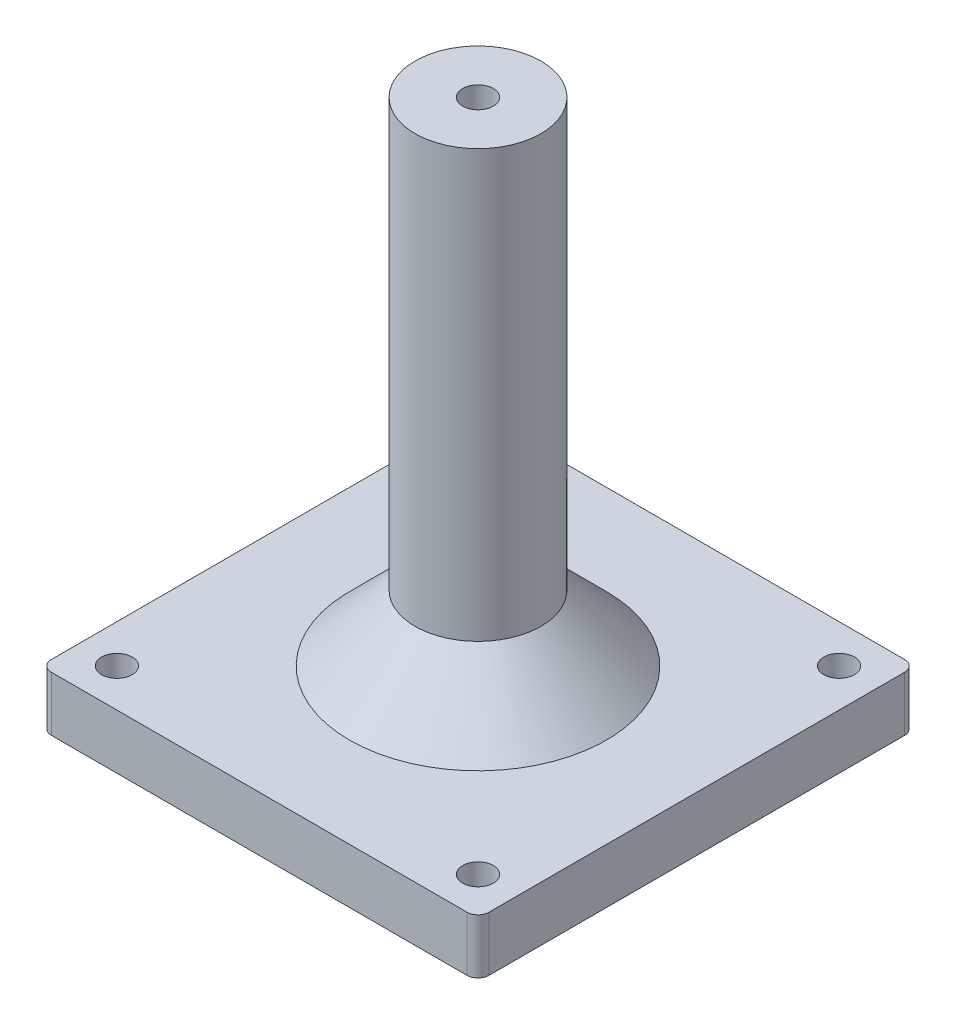
SolidWorks part; units mm, degrees
ref_plane "Front Plane" through (0, 0, 0) normal (0, 0, 1) x (1, 0, 0)
ref_plane "Top Plane" through (0, 0, 0) normal (0, 1, 0) x (1, 0, 0)
ref_plane "Right Plane" through (0, 0, 0) normal (1, 0, 0) x (0, 0, -1)
sketch "Sketch1" plane through (0, 0, 0) normal (0, 1, 0) x (1, 0, 0)
  line L1 (-20, 20) -> (20, 20)
  line L2 (-20, 20) -> (-20, -20)
  line L3 (-20, -20) -> (20, -20)
  line L4 (20, 20) -> (20, -20)
  line L5 (-20, 20) -> (20, -20) construction
  line L6 (-20, -20) -> (20, 20) construction
  circle A0 centre (0, 0) radius 6 construction
  circle A1 centre (0, 0) radius 10 construction
  point P0 (0, 0)
  dimension "D3" = 12
  dimension "D4" = 4
  dimension "D1" = 40
  dimension "D2" = 40
extrude "Boss-Extrude1" add sketch "Sketch1" along normal blind 5
sketch "Sketch3" plane through (0, 0, 0) normal (0, -1, 0) x (1, 0, 0)
  line L0 (-16.5, 16.5) -> (-16.5, -16.5) construction
  line L1 (-16.5, -16.5) -> (16.5, -16.5) construction
  line L2 (16.5, -16.5) -> (16.5, 16.5) construction
  line L3 (16.5, 16.5) -> (-16.5, 16.5) construction
  line L4 (20, -20) -> (20, 20)
  line L5 (20, 20) -> (-20, 20)
  line L6 (-20, 20) -> (-20, -20)
  line L7 (-20, -20) -> (20, -20)
  line L8 (20, -20) -> (20, 20) construction
  line L9 (20, 20) -> (-20, 20) construction
  line L10 (-20, 20) -> (-20, -20) construction
  line L11 (-20, -20) -> (20, -20) construction
  circle A0 centre (-16.5, -16.5) radius 1.4
  circle A1 centre (-16.5, 16.5) radius 1.4
  circle A2 centre (16.5, 16.5) radius 1.4
  circle A3 centre (16.5, -16.5) radius 1.4
  dimension "D3" = 2.8
  dimension "D1" = 0
  dimension "D2" = 3.5
extrude "Cut-Extrude1" cut sketch "Sketch3" against normal blind 10
sketch "Sketch4" plane through (0, 5, 0) normal (0, 1, 0) x (1, 0, 0)
  circle A0 centre (0, 0) radius 5.75
  dimension "D1" = 11.5
extrude "Boss-Extrude2" add sketch "Sketch4" along normal blind 45
sketch "Sketch5" plane through (0, 50, 0) normal (0, 1, 0) x (1, 0, 0)
  circle A0 centre (0, 0) radius 7.375
  dimension "D1" = 14.75
chamfer "Chamfer1" distance 6 angle 45 1 edges at (0, 5, 5.75)
sketch "Sketch6" plane through (0, 50, 0) normal (0, 1, 0) x (1, 0, 0)
  circle A0 centre (0, 0) radius 1.4
  dimension "D1" = 2.8
extrude "Cut-Extrude2" cut sketch "Sketch6" against normal blind 16
fillet "Fillet1" radius 1 4 edges at (-20, 2.5, -20) (20, 2.5, -20) (20, 2.5, 20) (-20, 2.5, 20)
